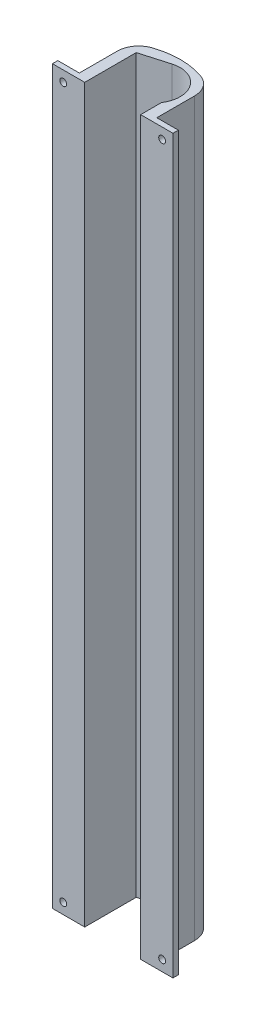
SolidWorks part; units mm, degrees
ref_plane "Front Plane" through (0, 0, 0) normal (0, 0, 1) x (1, 0, 0)
ref_plane "Top Plane" through (0, 0, 0) normal (0, 1, 0) x (1, 0, 0)
ref_plane "Right Plane" through (0, 0, 0) normal (1, 0, 0) x (0, 0, -1)
sketch "Sketch1" plane through (0, 0, 0) normal (0, 1, 0) x (1, 0, 0)
  line L0 (-20.574, -9.6521) -> (-4.162, -14.3967) construction
  line L1 (-4.1621, 14.3967) -> (-20.574, 9.652) construction
  line L2 (-20.574, 9.652) -> (-20.574, -9.6521) construction
  line L3 (-39.624, 20.7467) -> (-20.574, 20.7467) construction
  line L4 (-39.624, 20.7467) -> (-39.624, 17.5717) construction
  line L6 (12.446, 20.7467) -> (31.496, 20.7467) construction
  line L7 (-39.624, 17.5717) -> (-26.924, 17.5717) construction
  line L9 (-26.924, 17.5717) -> (-26.924, -12.8271) construction
  line L10 (31.496, 20.7467) -> (31.496, 17.5717) construction
  line L11 (31.496, 17.5717) -> (18.796, 17.5717) construction
  line L12 (18.796, 17.5717) -> (18.796, -12.8271) construction
  line L13 (-20.574, 9.652) -> (-20.574, 20.7467) construction
  line L14 (12.446, 20.7467) -> (12.446, 8.3478) construction
  line L15 (-69.4628, -37.4601) -> (67.1627, -37.4601) construction
  line L16 (-4.1621, -89.3169) -> (-20.574, -84.5722) construction
  line L17 (12.446, -95.6669) -> (12.446, -83.268)
  line L18 (-20.574, -84.5722) -> (-20.574, -95.6669)
  line L19 (18.796, -92.4919) -> (18.796, -62.0931)
  line L20 (31.496, -92.4919) -> (18.796, -92.4919)
  line L21 (31.496, -95.6669) -> (31.496, -92.4919)
  line L22 (-26.924, -92.4919) -> (-26.924, -62.0931)
  line L23 (-39.624, -92.4919) -> (-26.924, -92.4919)
  line L24 (12.446, -95.6669) -> (31.496, -95.6669)
  line L25 (-39.624, -95.6669) -> (-39.624, -92.4919)
  line L26 (-39.624, -95.6669) -> (-20.574, -95.6669)
  line L27 (-20.574, -84.5722) -> (-20.574, -65.2681)
  line L28 (-20.574, -65.2681) -> (-4.162, -60.5234)
  arc A0 (-4.162, -14.3967) -> (12.446, 8.3478) centre (0, 0) ccw construction
  arc A1 (-26.924, -12.8271) -> (18.796, -12.8271) centre (-4.064, 25.294) ccw construction
  arc A2 (12.446, 8.3478) -> (-4.1621, 14.3967) centre (0, 0) ccw construction
  arc A3 (12.446, -83.268) -> (-4.1621, -89.3169) centre (0, -74.9202) cw construction
  arc A4 (-26.924, -62.0931) -> (18.796, -62.0931) centre (-4.064, -100.2142) cw
  arc A5 (-4.162, -60.5234) -> (12.446, -83.268) centre (0, -74.9202) cw
  point P6 (12.446, 14.5473)
  dimension "D2" = 14.9863
  dimension "D14" = 37.4601
  dimension "D10" = 44.45
  dimension "D1" = 19.3041
  dimension "D3" = 16.4119
  dimension "D4" = 106.124
  dimension "D5" = 20.574
  dimension "D6" = 106.125
  dimension "D7" = 6.35
  dimension "D8" = 6.35
  dimension "D9" = 3.175
  dimension "D11" = 12.7
  dimension "D12" = 3.175
  dimension "D13" = 33.02
  dimension "D15" = 6.35
extrude "Boss-Extrude1" add sketch "Sketch1" along normal blind 431.8
fillet "Fillet2" radius 12.7 2 edges at (18.796, 215.9, 62.0931) (-26.924, 215.9, 62.0931)
sketch "Sketch2" plane through (0, 0, 92.4919) normal (0, 0, -1) x (-1, 0, 0)
  line L0 (-31.496, 0) -> (-18.796, 0) construction
  line L2 (39.624, 431.8) -> (39.624, 0) construction
  line L3 (-31.496, 431.8) -> (-18.796, 431.8) construction
  circle A0 centre (-25.146, 425.45) radius 2.032
  circle A1 centre (-25.146, 6.35) radius 2.032
  circle A2 centre (33.274, 425.45) radius 2.032
  circle A3 centre (33.274, 6.35) radius 2.032
  dimension "D1" = 4.064
  dimension "D2" = 6.35
  dimension "D3" = 6.35
  dimension "D4" = 6.35
  dimension "D5" = 6.35
extrude "Cut-Extrude1" cut sketch "Sketch2" against normal through all
